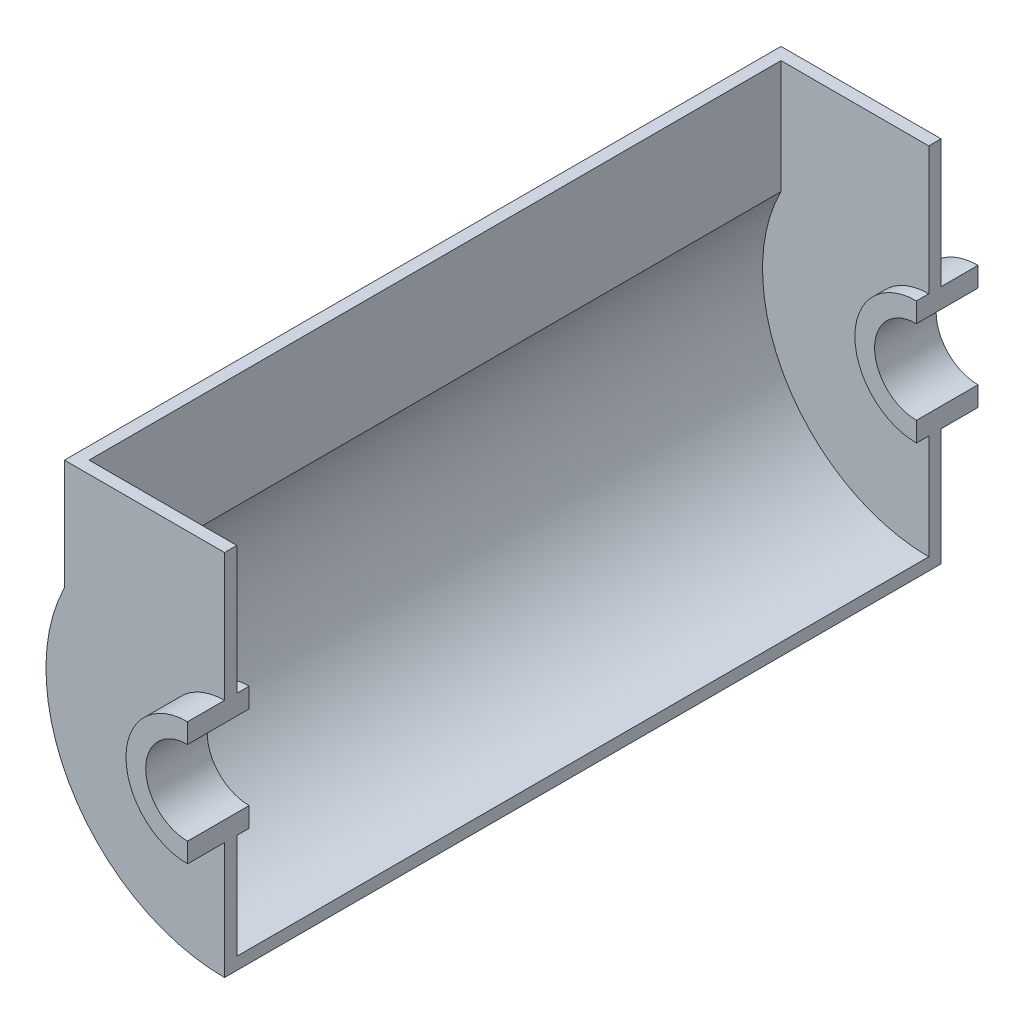
SolidWorks part; units mm, degrees
ref_plane "Front Plane" through (0, 0, 0) normal (0, 0, 1) x (1, 0, 0)
ref_plane "Top Plane" through (0, 0, 0) normal (0, 1, 0) x (1, 0, 0)
ref_plane "Right Plane" through (0, 0, 0) normal (1, 0, 0) x (0, 0, -1)
sketch "Sketch1" plane through (0, 0, 0) normal (0, 0, 1) x (1, 0, 0)
  line L0 (0, 25) -> (0, 17)
  line L1 (0, -17) -> (0, -25)
  arc A0 (0, 25) -> (0, -25) centre (0, 0) ccw
  arc A1 (0, 17) -> (0, -17) centre (0, 0) ccw
  dimension "D1" = 50
  dimension "D2" = 34
extrude "Boss-Extrude1" add sketch "Sketch1" along normal blind 20 and the other way blind 5
sketch "Sketch2" plane through (0, 0, 0) normal (0, 0, 1) x (1, 0, 0)
  line L0 (0, 25) -> (0, 77)
  line L1 (0, 77) -> (-65, 77)
  line L2 (-65, 77) -> (-65, 32.1131)
  line L3 (0, -25) -> (0, -72.5)
  arc A0 (0, 25) -> (0, -25) centre (0, 0) ccw construction
  arc A1 (0, 25) -> (0, -25) centre (0, 0) ccw
  arc A2 (-65, 32.1131) -> (0, -72.5) centre (0, 0) ccw
  dimension "D1" = 52
  dimension "D3" = 72.5
  dimension "D2" = 65
extrude "Boss-Extrude2" add sketch "Sketch2" along normal blind 5
ref_plane "Plane1" through (0, 0, -140.5) normal (0, 0, 1) x (1, 0, 0)
mirror "Mirror10" about plane through (0, 0, -140.5) normal (0, 0, 1) of bodies 102
sketch "Sketch3" plane through (0, 0, 0) normal (0, 0, -1) x (-1, 0, 0)
  line L0 (65, 77) -> (65, 32.1131) construction
  line L1 (65, 77) -> (65, 32.1131)
  line L2 (60, 77) -> (60, 30.9233)
  line L3 (0, -72.5) -> (0, -67.5)
  line L4 (65, 77) -> (60, 77)
  arc A0 (0, -72.5) -> (65, 32.1131) centre (0, 0) ccw construction
  arc A1 (0, -72.5) -> (65, 32.1131) centre (0, 0) ccw
  arc A2 (0, -67.5) -> (60, 30.9233) centre (0, 0) ccw
  dimension "D1" = 5
extrude "Boss-Extrude3" add sketch "Sketch3" along normal up to surface (281 mm away) up to face at (-30.6802, 15.924, -281)
